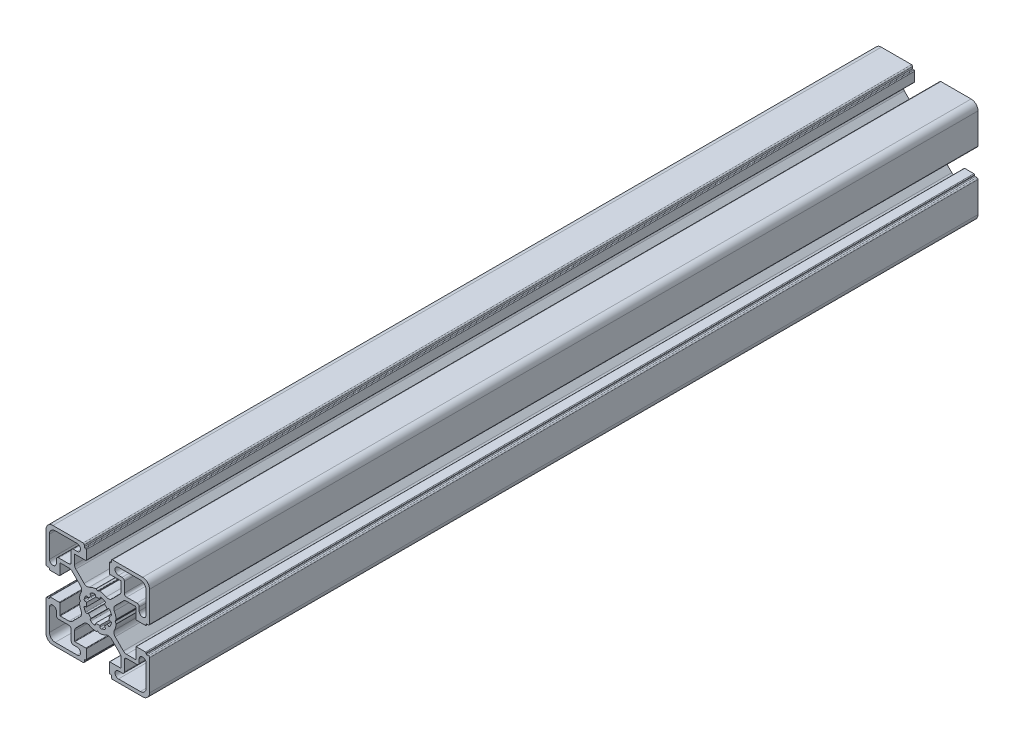
SolidWorks part; units mm, degrees
ref_plane "Front Plane" through (0, 0, 0) normal (0, 0, 1) x (1, 0, 0)
ref_plane "Top Plane" through (0, 0, 0) normal (0, 1, 0) x (1, 0, 0)
ref_plane "Right Plane" through (0, 0, 0) normal (1, 0, 0) x (0, 0, -1)
sketch "Sketch1" plane through (0, 0, 0) normal (0, 0, 1) x (1, 0, 0)
  line L0 (10.55, 18) -> (9, 18)
  line L1 (18.5, 21) -> (9, 21)
  line L2 (21, 9.0002) -> (21, 18.5)
  line L3 (18, 9.0002) -> (18, 10.55)
  line L4 (17, 11.55) -> (12.55, 11.55)
  line L5 (11.55, 12.55) -> (11.55, 17)
  line L6 (7.974, 0.7926) -> (7.5401, 0.0468)
  line L7 (-0.8674, 4.9242) -> (-0.9675, 5.4811)
  line L8 (-3.1913, 4.5626) -> (-2.864, 4.0985)
  line L9 (-4.0897, 2.8765) -> (-4.5668, 3.2082)
  line L10 (-5.4897, 0.9862) -> (-4.9205, 0.8878)
  line L11 (11.1298, 9.425) -> (7.5635, 5.8587)
  line L12 (16.3169, 9.9945) -> (12.5048, 9.9945)
  line L13 (16.5169, 5.2) -> (16.5169, 9.7945)
  line L14 (20.7196, 5) -> (16.7169, 5)
  line L15 (21.0196, 5.3) -> (21.0196, 5.5)
  line L16 (22, 5.8) -> (21.3196, 5.8)
  line L17 (22.5, 6.3) -> (22.5, 19.5)
  line L18 (19.5, 22.5) -> (6.3757, 22.5)
  line L19 (5.8757, 21.3) -> (5.8757, 22)
  line L20 (5.5757, 21) -> (5.3, 21)
  line L21 (5, 16.6668) -> (5, 20.7)
  line L22 (9.9054, 16.4668) -> (5.2, 16.4668)
  line L23 (10.1054, 12.4716) -> (10.1054, 16.2668)
  line L24 (5.9449, 7.4827) -> (9.5196, 11.0574)
  line L25 (0.1126, 7.6069) -> (0.7547, 7.9748)
  line L26 (5.4897, 0.9862) -> (4.9205, 0.8878)
  line L27 (4.0897, 2.8765) -> (4.5668, 3.2082)
  line L28 (3.1913, 4.5626) -> (2.864, 4.0985)
  line L29 (0.8674, 4.9242) -> (0.9675, 5.4811)
  line L30 (-10.55, -18) -> (-9, -18)
  line L31 (-18.5, -21) -> (-9, -21)
  line L32 (-21, -9.0002) -> (-21, -18.5)
  line L33 (-18, -9.0002) -> (-18, -10.55)
  line L34 (-17, -11.55) -> (-12.55, -11.55)
  line L35 (-11.55, -12.55) -> (-11.55, -17)
  line L36 (-7.974, -0.7926) -> (-7.5401, -0.0468)
  line L37 (-11.1298, -9.425) -> (-7.5635, -5.8587)
  line L38 (-16.3169, -9.9945) -> (-12.5048, -9.9945)
  line L39 (-16.5169, -5.2) -> (-16.5169, -9.7945)
  line L40 (-20.7196, -5) -> (-16.7169, -5)
  line L41 (-21.0196, -5.3) -> (-21.0196, -5.5)
  line L42 (-22, -5.8) -> (-21.3196, -5.8)
  line L43 (-22.5, -6.3) -> (-22.5, -19.5)
  line L44 (-19.5, -22.5) -> (-6.3757, -22.5)
  line L45 (-5.8757, -21.3) -> (-5.8757, -22)
  line L46 (-5.5757, -21) -> (-5.3, -21)
  line L47 (-5, -16.6668) -> (-5, -20.7)
  line L48 (-9.9054, -16.4668) -> (-5.2, -16.4668)
  line L49 (-10.1054, -12.4716) -> (-10.1054, -16.2668)
  line L50 (-5.9449, -7.4827) -> (-9.5196, -11.0574)
  line L51 (-0.1126, -7.6069) -> (-0.7547, -7.9748)
  line L52 (0.8674, -4.9242) -> (0.9675, -5.4811)
  line L53 (3.1913, -4.5626) -> (2.864, -4.0985)
  line L54 (4.0897, -2.8765) -> (4.5668, -3.2082)
  line L55 (5.4897, -0.9862) -> (4.9205, -0.8878)
  line L56 (0.1126, -7.6069) -> (0.7547, -7.9748)
  line L57 (5.9449, -7.4827) -> (9.5196, -11.0574)
  line L58 (10.1054, -12.4716) -> (10.1054, -16.2668)
  line L59 (9.9054, -16.4668) -> (5.2, -16.4668)
  line L60 (5, -16.6668) -> (5, -20.7)
  line L61 (5.5757, -21) -> (5.3, -21)
  line L62 (-0.1126, 7.6069) -> (-0.7547, 7.9748)
  line L63 (-5.9449, 7.4827) -> (-9.5196, 11.0574)
  line L64 (-10.1054, 12.4716) -> (-10.1054, 16.2668)
  line L65 (-9.9054, 16.4668) -> (-5.2, 16.4668)
  line L66 (-5, 16.6668) -> (-5, 20.7)
  line L67 (-5.5757, 21) -> (-5.3, 21)
  line L68 (-5.8757, 21.3) -> (-5.8757, 22)
  line L69 (-19.5, 22.5) -> (-6.3757, 22.5)
  line L70 (-22.5, 6.3) -> (-22.5, 19.5)
  line L71 (-22, 5.8) -> (-21.3196, 5.8)
  line L72 (-21.0196, 5.3) -> (-21.0196, 5.5)
  line L73 (-20.7196, 5) -> (-16.7169, 5)
  line L74 (-16.5169, 5.2) -> (-16.5169, 9.7945)
  line L75 (-16.3169, 9.9945) -> (-12.5048, 9.9945)
  line L76 (-11.1298, 9.425) -> (-7.5635, 5.8587)
  line L77 (-7.974, 0.7926) -> (-7.5401, 0.0468)
  line L78 (5.8757, -21.3) -> (5.8757, -22)
  line L79 (19.5, -22.5) -> (6.3757, -22.5)
  line L80 (22.5, -6.3) -> (22.5, -19.5)
  line L81 (22, -5.8) -> (21.3196, -5.8)
  line L82 (21.0196, -5.3) -> (21.0196, -5.5)
  line L83 (20.7196, -5) -> (16.7169, -5)
  line L84 (16.5169, -5.2) -> (16.5169, -9.7945)
  line L85 (16.3169, -9.9945) -> (12.5048, -9.9945)
  line L86 (11.1298, -9.425) -> (7.5635, -5.8587)
  line L87 (-5.4897, -0.9862) -> (-4.9205, -0.8878)
  line L88 (-4.0897, -2.8765) -> (-4.5668, -3.2082)
  line L89 (-3.1913, -4.5626) -> (-2.864, -4.0985)
  line L90 (-0.8674, -4.9242) -> (-0.9675, -5.4811)
  line L91 (7.974, -0.7926) -> (7.5401, -0.0468)
  line L92 (-11.55, 12.55) -> (-11.55, 17)
  line L93 (-17, 11.55) -> (-12.55, 11.55)
  line L94 (-18, 9.0002) -> (-18, 10.55)
  line L95 (-21, 9.0002) -> (-21, 18.5)
  line L96 (-18.5, 21) -> (-9, 21)
  line L97 (-10.55, 18) -> (-9, 18)
  line L98 (11.55, -12.55) -> (11.55, -17)
  line L99 (17, -11.55) -> (12.55, -11.55)
  line L100 (18, -9.0002) -> (18, -10.55)
  line L101 (21, -9.0002) -> (21, -18.5)
  line L102 (18.5, -21) -> (9, -21)
  line L103 (10.55, -18) -> (9, -18)
  line L104 (-33.3633, 0) -> (37.7265, 0) construction
  line L105 (0, 32.2957) -> (0, -36.0465) construction
  arc A0 (9, 18) -> (9, 21) centre (9, 19.5) cw
  arc A1 (18.5, 21) -> (21, 18.5) centre (18.5, 18.5) cw
  arc A2 (21, 9.0002) -> (18, 9.0002) centre (19.5, 9.0002) cw
  arc A3 (17, 11.55) -> (18, 10.55) centre (17, 10.55) cw
  arc A4 (12.55, 11.55) -> (11.55, 12.55) centre (12.55, 12.55) cw
  arc A5 (10.55, 18) -> (11.55, 17) centre (10.55, 17) cw
  arc A6 (7.5313, 0) -> (7.5401, 0.0468) centre (7.7309, -0.013) cw
  arc A7 (8, 0.9141) -> (7.974, 0.7926) centre (7.8011, 0.8932) cw
  arc A8 (7.2004, 3.6119) -> (8, 0.9141) centre (0.0496, 0.0249) cw
  arc A9 (7.2004, 3.6119) -> (7.5635, 5.8587) centre (8.9385, 4.4837) cw
  arc A10 (11.1298, 9.425) -> (12.5048, 9.9945) centre (12.5048, 8.05) cw
  arc A11 (16.3169, 9.9945) -> (16.5169, 9.7945) centre (16.3169, 9.7945) cw
  arc A12 (16.7169, 5) -> (16.5169, 5.2) centre (16.7169, 5.2) cw
  arc A13 (21.0196, 5.3) -> (20.7196, 5) centre (20.7196, 5.3) cw
  arc A14 (0.8674, 4.9242) -> (-0.8674, 4.9242) centre (0, 0) ccw
  arc A15 (-0.9675, 5.4811) -> (-1.5951, 5.8941) centre (-1.4627, 5.4119) ccw
  arc A16 (-1.5951, 5.8941) -> (-3.0444, 5.2994) centre (-0.0235, 0) ccw
  arc A17 (-3.0444, 5.2994) -> (-3.1913, 4.5626) centre (-2.7943, 4.8665) ccw
  arc A18 (-2.864, 4.0985) -> (-4.0897, 2.8765) centre (0, 0) ccw
  arc A19 (-4.5668, 3.2082) -> (-5.3025, 3.0565) centre (-4.868, 2.8091) ccw
  arc A20 (-5.3025, 3.0565) -> (-5.9068, 1.6112) centre (-0.0235, 0) ccw
  arc A21 (-5.9068, 1.6112) -> (-5.4897, 0.9862) centre (-5.4239, 1.4819) ccw
  arc A22 (-4.9205, 0.8878) -> (-5, 0) centre (0, 0) ccw
  arc A23 (21.0196, 5.5) -> (21.3196, 5.8) centre (21.3196, 5.5) cw
  arc A24 (22.5, 6.3) -> (22, 5.8) centre (22, 6.3) cw
  arc A25 (19.5, 22.5) -> (22.5, 19.5) centre (19.5, 19.5) cw
  arc A26 (5.8757, 22) -> (6.3757, 22.5) centre (6.3757, 22) cw
  arc A27 (5.8757, 21.3) -> (5.5757, 21) centre (5.5757, 21.3) cw
  arc A28 (5, 20.7) -> (5.3, 21) centre (5.3, 20.7) cw
  arc A29 (5.2, 16.4668) -> (5, 16.6668) centre (5.2, 16.6668) cw
  arc A30 (9.9054, 16.4668) -> (10.1054, 16.2668) centre (9.9054, 16.2668) cw
  arc A31 (10.1054, 12.4716) -> (9.5196, 11.0574) centre (8.1054, 12.4716) cw
  arc A32 (5.9449, 7.4827) -> (3.6665, 7.1733) centre (4.5855, 8.9496) cw
  arc A33 (0.8764, 8) -> (3.6665, 7.1733) centre (0.0235, 0) cw
  arc A34 (0.7547, 7.9748) -> (0.8764, 8) centre (0.8542, 7.8013) cw
  arc A35 (0.1126, 7.6069) -> (0, 7.531) centre (-0.0489, 7.7249) cw
  arc A36 (4.9205, 0.8878) -> (5, 0) centre (0, 0) cw
  arc A37 (5.9068, 1.6112) -> (5.4897, 0.9862) centre (5.4239, 1.4819) cw
  arc A38 (5.3025, 3.0565) -> (5.9068, 1.6112) centre (0.0235, 0) cw
  arc A39 (4.5668, 3.2082) -> (5.3025, 3.0565) centre (4.868, 2.8091) cw
  arc A40 (2.864, 4.0985) -> (4.0897, 2.8765) centre (0, 0) cw
  arc A41 (3.0444, 5.2994) -> (3.1913, 4.5626) centre (2.7943, 4.8665) cw
  arc A42 (1.5951, 5.8941) -> (3.0444, 5.2994) centre (0.0235, 0) cw
  arc A43 (0.9675, 5.4811) -> (1.5951, 5.8941) centre (1.4627, 5.4119) cw
  arc A44 (-9, -18) -> (-9, -21) centre (-9, -19.5) cw
  arc A45 (-18.5, -21) -> (-21, -18.5) centre (-18.5, -18.5) cw
  arc A46 (-21, -9.0002) -> (-18, -9.0002) centre (-19.5, -9.0002) cw
  arc A47 (-17, -11.55) -> (-18, -10.55) centre (-17, -10.55) cw
  arc A48 (-12.55, -11.55) -> (-11.55, -12.55) centre (-12.55, -12.55) cw
  arc A49 (-10.55, -18) -> (-11.55, -17) centre (-10.55, -17) cw
  arc A50 (-7.5313, 0) -> (-7.5401, -0.0468) centre (-7.7309, 0.013) cw
  arc A51 (-8, -0.9141) -> (-7.974, -0.7926) centre (-7.8011, -0.8932) cw
  arc A52 (-7.2004, -3.6119) -> (-8, -0.9141) centre (-0.0496, -0.0249) cw
  arc A53 (-7.2004, -3.6119) -> (-7.5635, -5.8587) centre (-8.9385, -4.4837) cw
  arc A54 (-11.1298, -9.425) -> (-12.5048, -9.9945) centre (-12.5048, -8.05) cw
  arc A55 (-16.3169, -9.9945) -> (-16.5169, -9.7945) centre (-16.3169, -9.7945) cw
  arc A56 (-16.7169, -5) -> (-16.5169, -5.2) centre (-16.7169, -5.2) cw
  arc A57 (-21.0196, -5.3) -> (-20.7196, -5) centre (-20.7196, -5.3) cw
  arc A58 (-21.0196, -5.5) -> (-21.3196, -5.8) centre (-21.3196, -5.5) cw
  arc A59 (-22.5, -6.3) -> (-22, -5.8) centre (-22, -6.3) cw
  arc A60 (-19.5, -22.5) -> (-22.5, -19.5) centre (-19.5, -19.5) cw
  arc A61 (-5.8757, -22) -> (-6.3757, -22.5) centre (-6.3757, -22) cw
  arc A62 (-5.8757, -21.3) -> (-5.5757, -21) centre (-5.5757, -21.3) cw
  arc A63 (-5, -20.7) -> (-5.3, -21) centre (-5.3, -20.7) cw
  arc A64 (-5.2, -16.4668) -> (-5, -16.6668) centre (-5.2, -16.6668) cw
  arc A65 (-9.9054, -16.4668) -> (-10.1054, -16.2668) centre (-9.9054, -16.2668) cw
  arc A66 (-10.1054, -12.4716) -> (-9.5196, -11.0574) centre (-8.1054, -12.4716) cw
  arc A67 (-5.9449, -7.4827) -> (-3.6665, -7.1733) centre (-4.5855, -8.9496) cw
  arc A68 (-0.8764, -8) -> (-3.6665, -7.1733) centre (-0.0235, 0) cw
  arc A69 (-0.7547, -7.9748) -> (-0.8764, -8) centre (-0.8542, -7.8013) cw
  arc A70 (-0.1126, -7.6069) -> (0, -7.531) centre (0.0489, -7.7249) cw
  arc A71 (0.9675, -5.4811) -> (1.5951, -5.8941) centre (1.4627, -5.4119) ccw
  arc A72 (1.5951, -5.8941) -> (3.0444, -5.2994) centre (0.0235, 0) ccw
  arc A73 (3.0444, -5.2994) -> (3.1913, -4.5626) centre (2.7943, -4.8665) ccw
  arc A74 (2.864, -4.0985) -> (4.0897, -2.8765) centre (0, 0) ccw
  arc A75 (4.5668, -3.2082) -> (5.3025, -3.0565) centre (4.868, -2.8091) ccw
  arc A76 (5.3025, -3.0565) -> (5.9068, -1.6112) centre (0.0235, 0) ccw
  arc A77 (5.9068, -1.6112) -> (5.4897, -0.9862) centre (5.4239, -1.4819) ccw
  arc A78 (4.9205, -0.8878) -> (5, 0) centre (0, 0) ccw
  arc A79 (0.1126, -7.6069) -> (0, -7.531) centre (-0.0489, -7.7249) ccw
  arc A80 (0.7547, -7.9748) -> (0.8764, -8) centre (0.8542, -7.8013) ccw
  arc A81 (0.8764, -8) -> (3.6665, -7.1733) centre (0.0235, 0) ccw
  arc A82 (5.9449, -7.4827) -> (3.6665, -7.1733) centre (4.5855, -8.9496) ccw
  arc A83 (10.1054, -12.4716) -> (9.5196, -11.0574) centre (8.1054, -12.4716) ccw
  arc A84 (9.9054, -16.4668) -> (10.1054, -16.2668) centre (9.9054, -16.2668) ccw
  arc A85 (5.2, -16.4668) -> (5, -16.6668) centre (5.2, -16.6668) ccw
  arc A86 (5, -20.7) -> (5.3, -21) centre (5.3, -20.7) ccw
  arc A87 (5.8757, -21.3) -> (5.5757, -21) centre (5.5757, -21.3) ccw
  arc A88 (-0.1126, 7.6069) -> (0, 7.531) centre (0.0489, 7.7249) ccw
  arc A89 (-0.7547, 7.9748) -> (-0.8764, 8) centre (-0.8542, 7.8013) ccw
  arc A90 (-0.8764, 8) -> (-3.6665, 7.1733) centre (-0.0235, 0) ccw
  arc A91 (-5.9449, 7.4827) -> (-3.6665, 7.1733) centre (-4.5855, 8.9496) ccw
  arc A92 (-10.1054, 12.4716) -> (-9.5196, 11.0574) centre (-8.1054, 12.4716) ccw
  arc A93 (-9.9054, 16.4668) -> (-10.1054, 16.2668) centre (-9.9054, 16.2668) ccw
  arc A94 (-5.2, 16.4668) -> (-5, 16.6668) centre (-5.2, 16.6668) ccw
  arc A95 (-5, 20.7) -> (-5.3, 21) centre (-5.3, 20.7) ccw
  arc A96 (-5.8757, 21.3) -> (-5.5757, 21) centre (-5.5757, 21.3) ccw
  arc A97 (-5.8757, 22) -> (-6.3757, 22.5) centre (-6.3757, 22) ccw
  arc A98 (-19.5, 22.5) -> (-22.5, 19.5) centre (-19.5, 19.5) ccw
  arc A99 (-22.5, 6.3) -> (-22, 5.8) centre (-22, 6.3) ccw
  arc A100 (-21.0196, 5.5) -> (-21.3196, 5.8) centre (-21.3196, 5.5) ccw
  arc A101 (-21.0196, 5.3) -> (-20.7196, 5) centre (-20.7196, 5.3) ccw
  arc A102 (-16.7169, 5) -> (-16.5169, 5.2) centre (-16.7169, 5.2) ccw
  arc A103 (-16.3169, 9.9945) -> (-16.5169, 9.7945) centre (-16.3169, 9.7945) ccw
  arc A104 (-11.1298, 9.425) -> (-12.5048, 9.9945) centre (-12.5048, 8.05) ccw
  arc A105 (-7.2004, 3.6119) -> (-7.5635, 5.8587) centre (-8.9385, 4.4837) ccw
  arc A106 (-7.2004, 3.6119) -> (-8, 0.9141) centre (-0.0496, 0.0249) ccw
  arc A107 (-8, 0.9141) -> (-7.974, 0.7926) centre (-7.8011, 0.8932) ccw
  arc A108 (-7.5313, 0) -> (-7.5401, 0.0468) centre (-7.7309, -0.013) ccw
  arc A109 (5.8757, -22) -> (6.3757, -22.5) centre (6.3757, -22) ccw
  arc A110 (19.5, -22.5) -> (22.5, -19.5) centre (19.5, -19.5) ccw
  arc A111 (22.5, -6.3) -> (22, -5.8) centre (22, -6.3) ccw
  arc A112 (21.0196, -5.5) -> (21.3196, -5.8) centre (21.3196, -5.5) ccw
  arc A113 (-4.9205, -0.8878) -> (-5, 0) centre (0, 0) cw
  arc A114 (-5.9068, -1.6112) -> (-5.4897, -0.9862) centre (-5.4239, -1.4819) cw
  arc A115 (-5.3025, -3.0565) -> (-5.9068, -1.6112) centre (-0.0235, 0) cw
  arc A116 (-4.5668, -3.2082) -> (-5.3025, -3.0565) centre (-4.868, -2.8091) cw
  arc A117 (-2.864, -4.0985) -> (-4.0897, -2.8765) centre (0, 0) cw
  arc A118 (-3.0444, -5.2994) -> (-3.1913, -4.5626) centre (-2.7943, -4.8665) cw
  arc A119 (-1.5951, -5.8941) -> (-3.0444, -5.2994) centre (-0.0235, 0) cw
  arc A120 (-0.9675, -5.4811) -> (-1.5951, -5.8941) centre (-1.4627, -5.4119) cw
  arc A121 (0.8674, -4.9242) -> (-0.8674, -4.9242) centre (0, 0) cw
  arc A122 (21.0196, -5.3) -> (20.7196, -5) centre (20.7196, -5.3) ccw
  arc A123 (16.7169, -5) -> (16.5169, -5.2) centre (16.7169, -5.2) ccw
  arc A124 (-10.55, 18) -> (-11.55, 17) centre (-10.55, 17) ccw
  arc A125 (-12.55, 11.55) -> (-11.55, 12.55) centre (-12.55, 12.55) ccw
  arc A126 (-17, 11.55) -> (-18, 10.55) centre (-17, 10.55) ccw
  arc A127 (-21, 9.0002) -> (-18, 9.0002) centre (-19.5, 9.0002) ccw
  arc A128 (-18.5, 21) -> (-21, 18.5) centre (-18.5, 18.5) ccw
  arc A129 (-9, 18) -> (-9, 21) centre (-9, 19.5) ccw
  arc A130 (16.3169, -9.9945) -> (16.5169, -9.7945) centre (16.3169, -9.7945) ccw
  arc A131 (11.1298, -9.425) -> (12.5048, -9.9945) centre (12.5048, -8.05) ccw
  arc A132 (7.2004, -3.6119) -> (7.5635, -5.8587) centre (8.9385, -4.4837) ccw
  arc A133 (7.2004, -3.6119) -> (8, -0.9141) centre (0.0496, -0.0249) ccw
  arc A134 (8, -0.9141) -> (7.974, -0.7926) centre (7.8011, -0.8932) ccw
  arc A135 (7.5313, 0) -> (7.5401, -0.0468) centre (7.7309, 0.013) ccw
  arc A136 (10.55, -18) -> (11.55, -17) centre (10.55, -17) ccw
  arc A137 (12.55, -11.55) -> (11.55, -12.55) centre (12.55, -12.55) ccw
  arc A138 (17, -11.55) -> (18, -10.55) centre (17, -10.55) ccw
  arc A139 (21, -9.0002) -> (18, -9.0002) centre (19.5, -9.0002) ccw
  arc A140 (18.5, -21) -> (21, -18.5) centre (18.5, -18.5) ccw
  arc A141 (9, -18) -> (9, -21) centre (9, -19.5) ccw
  dimension "D6" = 12.2
  dimension "D8" = 10
  dimension "D1" = 10
  dimension "D2" = 45
  dimension "D3" = 45
  dimension "D4" = 10
  dimension "D5" = 14.5
  dimension "D7" = 22.5
extrude "Base-Extrude" add sketch "Sketch1" against normal blind 360
sketch "Sketch2" plane through (22.5, 0, 0) normal (1, 0, 0) x (0, 0, -1)
  line L0 (0, 6.3) -> (0, 19.5) construction
  circle A0 centre (85, 0) radius 4.2
  circle A1 centre (45, 0) radius 4.2
  dimension "D1" = 85
  dimension "D2" = 40
extrude "Cut-Extrude1" cut sketch "Sketch2" against normal blind 164
